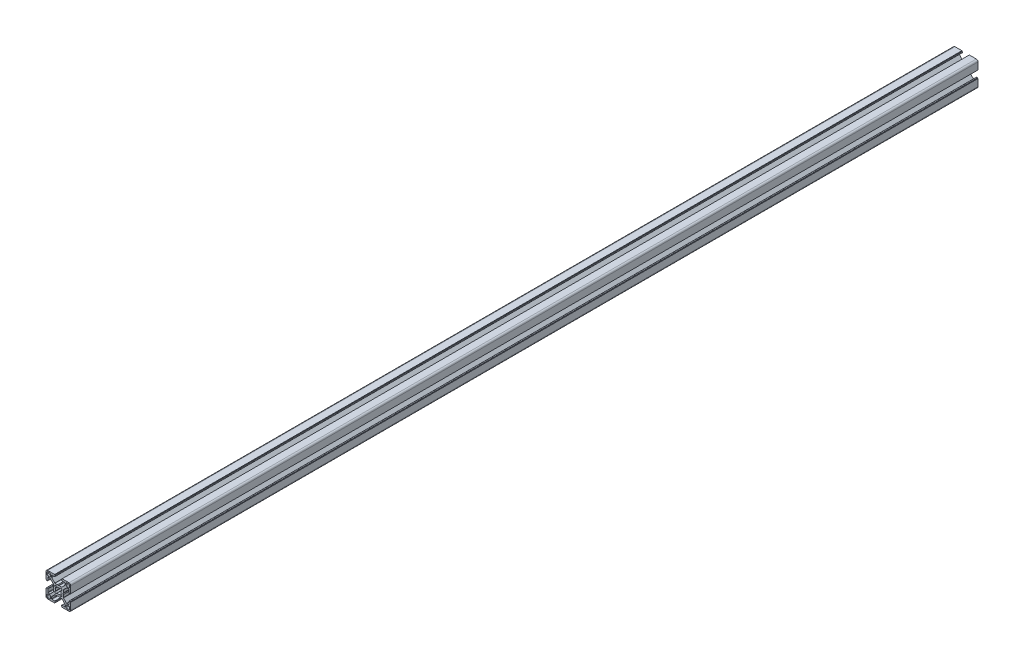
SolidWorks part; units mm, degrees
ref_plane "Front Plane" through (0, 0, 0) normal (0, 0, 1) x (1, 0, 0)
ref_plane "Top Plane" through (0, 0, 0) normal (0, 1, 0) x (1, 0, 0)
ref_plane "Right Plane" through (0, 0, 0) normal (1, 0, 0) x (0, 0, -1)
sketch "Sketch1" plane through (0, 0, 0) normal (0, 0, 1) x (1, 0, 0)
  line L0 (-15, 0) -> (15, 0) construction
  line L1 (0, -15) -> (0, 15) construction
  line L2 (-4.5, 15) -> (4.5, 15) construction
  line L3 (-4, -15) -> (4, -15) construction
  line L4 (-4.5, 15) -> (-4.5, 14.5)
  line L5 (-4.5, 14.5) -> (-4, 14.5)
  line L6 (-4, 14.5) -> (-4, 13.29)
  line L7 (-4.5, 12.79) -> (-7.7675, 12.79)
  line L8 (-8.2675, 12.29) -> (-8.2675, 10.2707)
  line L9 (-8.1211, 9.9171) -> (-4.3504, 6.1464)
  line L10 (-3.9968, 6) -> (0, 6)
  line L11 (0, 0) -> (-15, 15) construction
  line L12 (-4.5, 15) -> (-12.968, 15)
  line L14 (-12.705, 9.5135) -> (-10.5135, 9.5135)
  line L15 (-13.705, 10.5135) -> (-13.705, 12.705)
  line L16 (-12.705, 13.705) -> (-10.5135, 13.705)
  line L17 (-9.5135, 10.5135) -> (-9.5135, 12.705)
  line L18 (-13.705, 9.5135) -> (-9.5135, 13.705) construction
  line L19 (-13.705, 13.705) -> (-9.5135, 9.5135) construction
  line L20 (-3.1568, 4.5038) -> (-1.5303, 3.1477) construction
  line L21 (-4.5038, 3.1568) -> (-3.1477, 1.5303) construction
  line L22 (-6, 3.9968) -> (-6, 0)
  line L23 (-9.9171, 8.1211) -> (-6.1464, 4.3504)
  line L24 (-15, 4.5) -> (-15, 12.968)
  line L25 (-12.29, 8.2675) -> (-10.2707, 8.2675)
  line L26 (-12.79, 4.5) -> (-12.79, 7.7675)
  line L27 (-14.5, 4) -> (-13.29, 4)
  line L28 (-14.5, 4.5) -> (-14.5, 4)
  line L29 (-15, 4.5) -> (-14.5, 4.5)
  circle A0 centre (0, 0) radius 3.5
  arc A1 (-12.968, 15) -> (-15, 12.968) centre (-12.968, 12.968) ccw
  circle A2 centre (0, 0) radius 5.5 construction
  arc A3 (-10.5135, 9.5135) -> (-9.5135, 10.5135) centre (-10.5135, 10.5135) ccw
  arc A4 (-13.705, 12.705) -> (-12.705, 13.705) centre (-12.705, 12.705) cw
  arc A5 (-10.5135, 13.705) -> (-9.5135, 12.705) centre (-10.5135, 12.705) cw
  arc A6 (-12.705, 9.5135) -> (-13.705, 10.5135) centre (-12.705, 10.5135) cw
  arc A7 (-12.79, 4.5) -> (-13.29, 4) centre (-13.29, 4.5) cw
  arc A8 (-12.29, 8.2675) -> (-12.79, 7.7675) centre (-12.29, 7.7675) ccw
  arc A9 (-9.9171, 8.1211) -> (-10.2707, 8.2675) centre (-10.2707, 7.7675) ccw
  arc A10 (-6, 3.9968) -> (-6.1464, 4.3504) centre (-6.5, 3.9968) ccw
  arc A11 (-4.3504, 6.1464) -> (-3.9968, 6) centre (-3.9968, 6.5) ccw
  arc A12 (-4, 13.29) -> (-4.5, 12.79) centre (-4.5, 13.29) cw
  arc A13 (-7.7675, 12.79) -> (-8.2675, 12.29) centre (-7.7675, 12.29) ccw
  arc A14 (-8.2675, 10.2707) -> (-8.1211, 9.9171) centre (-7.7675, 10.2707) ccw
  point P4 (0, 0)
  point P8 (0, 0)
  point P13 (0, 15)
  point P15 (0, -15)
  point P16 (0, 6)
  point P23 (-11.6092, 11.6093)
  point P26 (0, 6)
  point P62 (-12.79, 4)
  point P65 (-12.79, 8.2675)
  point P68 (-10.0636, 8.2675)
  point P71 (-6, 4.2039)
  point P74 (-4.2039, 6)
  point P77 (-4, 12.79)
  point P80 (-8.2675, 12.79)
  point P83 (-8.2675, 10.0636)
  dimension "Center Hole Diameter" = 7
  dimension "D11" = 2.032
  dimension "D9" = 11
  dimension "D13" = 1
  dimension "D14" = 0.5
  dimension "Rail Height" = 30
  dimension "Rail Width" = 30
  dimension "T-Slot Width" = 8
  dimension "T-Slot Depth" = 9
  dimension "D1" = 9
  dimension "D2" = 45
  dimension "D3" = 8
  dimension "D4" = 2.21
  dimension "D5" = 16.535
  dimension "D7" = 2.54
  dimension "D6" = 1.295
  dimension "D8" = 1.246
  dimension "D10" = 10.36
  dimension "D12" = 1.905
sketch "Sketch2" plane through (0, 0, 0) normal (1, 0, 0) x (0, 0, -1)
  line L0 (-76.2, 0) -> (76.2, 0) construction
  line L2 (0, -15) -> (0, 15) construction
  line L3 (0, -15) -> (0, 15) construction
  line L4 (-76.2, -15) -> (-76.2, 15) construction
  line L5 (76.2, -15) -> (76.2, 15) construction
  point P0 (-38.7, 0)
  point P3 (0, 0)
  point P4 (38.7, 0)
  point P12 (-76.2, 0)
  point P14 (76.2, 0)
  dimension "Length" = 152.4
  dimension "D1" = 37.5
sketch "Sketch3" plane through (0, 0, 0) normal (0, 0, 1) x (1, 0, 0)
  line L0 (-4.5038, 3.1568) -> (-3.1477, 1.5303)
  line L1 (0, 3.5) -> (0, 5.5)
  line L2 (-5.5, 0) -> (-3.5, 0)
  line L7 (-6, 3.9968) -> (-6, 0) construction
  line L31 (-9.9171, 8.1211) -> (-6.1464, 4.3504) construction
  line L117 (-12.29, 8.2675) -> (-10.2707, 8.2675) construction
  line L118 (-12.79, 4.5) -> (-12.79, 7.7675) construction
  line L157 (-12.705, 9.5135) -> (-10.5135, 9.5135)
  line L158 (-9.5135, 10.5135) -> (-9.5135, 12.705)
  line L163 (-10.5135, 13.705) -> (-12.705, 13.705)
  line L164 (-13.705, 12.705) -> (-13.705, 10.5135)
  line L165 (-12.705, 9.5135) -> (-10.5135, 9.5135)
  line L166 (-9.5135, 10.5135) -> (-9.5135, 12.705)
  line L167 (-10.5135, 13.705) -> (-12.705, 13.705)
  line L168 (-13.705, 12.705) -> (-13.705, 10.5135)
  line L169 (-14.5, 4) -> (-13.29, 4) construction
  line L170 (-14.5, 4.5) -> (-14.5, 4) construction
  line L171 (-15, 4.5) -> (-14.5, 4.5) construction
  line L172 (-15, 4.5) -> (-15, 12.968) construction
  line L173 (-4.5, 15) -> (-12.968, 15) construction
  line L174 (-4.5, 15) -> (-4.5, 14.5) construction
  line L175 (-4.5, 14.5) -> (-4, 14.5) construction
  line L176 (-4, 14.5) -> (-4, 13.29) construction
  line L177 (-4.5, 12.79) -> (-7.7675, 12.79) construction
  line L178 (-8.2675, 12.29) -> (-8.2675, 10.2707) construction
  line L179 (-8.1211, 9.9171) -> (-4.3504, 6.1464) construction
  line L180 (-3.9968, 6) -> (0, 6) construction
  line L181 (-6, 3.9968) -> (-6, 0.866)
  line L182 (-9.9171, 8.1211) -> (-6.1464, 4.3504)
  line L183 (-12.29, 8.2675) -> (-10.2707, 8.2675)
  line L184 (-12.79, 4.5) -> (-12.79, 7.7675)
  line L185 (-14.5, 4) -> (-13.29, 4)
  line L186 (-14.5, 4.5) -> (-14.5, 4)
  line L187 (-15, 4.5) -> (-14.5, 4.5)
  line L188 (-15, 4.5) -> (-15, 12.968)
  line L189 (-4.5, 15) -> (-12.968, 15)
  line L190 (-4.5, 15) -> (-4.5, 14.5)
  line L191 (-4.5, 14.5) -> (-4, 14.5)
  line L192 (-4, 14.5) -> (-4, 13.29)
  line L193 (-4.5, 12.79) -> (-7.7675, 12.79)
  line L194 (-8.2675, 12.29) -> (-8.2675, 10.2707)
  line L195 (-8.1211, 9.9171) -> (-4.3504, 6.1464)
  line L196 (-3.9968, 6) -> (-0.866, 6)
  line L197 (-0.866, 6) -> (0, 5.5)
  line L198 (0, -15) -> (0, 15) construction
  line L199 (0, 0) -> (-15, 15) construction
  line L200 (0, 0) -> (-15, 15) construction
  line L201 (-3.1568, 4.5038) -> (-1.5303, 3.1477) construction
  line L202 (-3.1568, 4.5038) -> (-1.5303, 3.1477)
  line L203 (-6, 0.866) -> (-5.5, 0)
  line L204 (-15, 0) -> (15, 0) construction
  line L205 (-15, 0) -> (15, 0) construction
  line L206 (0, -15) -> (0, 15) construction
  arc A0 (-3.5, 0) -> (-3.1477, 1.5303) centre (0, 0) cw
  arc A10 (-6, 3.9968) -> (-6.1464, 4.3504) centre (-6.5, 3.9968) ccw construction
  circle A16 centre (0, 0) radius 3.5
  arc A18 (0, 3.5) -> (-1.5303, 3.1477) centre (0, 0) ccw
  arc A20 (-9.9171, 8.1211) -> (-10.2707, 8.2675) centre (-10.2707, 7.7675) ccw construction
  arc A22 (-12.29, 8.2675) -> (-12.79, 7.7675) centre (-12.29, 7.7675) ccw construction
  arc A28 (-13.29, 4) -> (-12.79, 4.5) centre (-13.29, 4.5) ccw construction
  arc A29 (-10.5135, 9.5135) -> (-9.5135, 10.5135) centre (-10.5135, 10.5135) ccw
  arc A30 (-9.5135, 12.705) -> (-10.5135, 13.705) centre (-10.5135, 12.705) ccw
  arc A31 (-12.705, 13.705) -> (-13.705, 12.705) centre (-12.705, 12.705) ccw
  arc A32 (-13.705, 10.5135) -> (-12.705, 9.5135) centre (-12.705, 10.5135) ccw
  arc A33 (-10.5135, 9.5135) -> (-9.5135, 10.5135) centre (-10.5135, 10.5135) ccw
  arc A34 (-9.5135, 12.705) -> (-10.5135, 13.705) centre (-10.5135, 12.705) ccw
  arc A35 (-12.705, 13.705) -> (-13.705, 12.705) centre (-12.705, 12.705) ccw
  arc A36 (-13.705, 10.5135) -> (-12.705, 9.5135) centre (-12.705, 10.5135) ccw
  arc A37 (-12.968, 15) -> (-15, 12.968) centre (-12.968, 12.968) ccw construction
  arc A38 (-4.5, 12.79) -> (-4, 13.29) centre (-4.5, 13.29) ccw construction
  arc A39 (-7.7675, 12.79) -> (-8.2675, 12.29) centre (-7.7675, 12.29) ccw construction
  arc A40 (-8.2675, 10.2707) -> (-8.1211, 9.9171) centre (-7.7675, 10.2707) ccw construction
  arc A41 (-4.3504, 6.1464) -> (-3.9968, 6) centre (-3.9968, 6.5) ccw construction
  arc A42 (-6, 3.9968) -> (-6.1464, 4.3504) centre (-6.5, 3.9968) ccw
  arc A43 (-9.9171, 8.1211) -> (-10.2707, 8.2675) centre (-10.2707, 7.7675) ccw
  arc A44 (-12.29, 8.2675) -> (-12.79, 7.7675) centre (-12.29, 7.7675) ccw
  arc A45 (-13.29, 4) -> (-12.79, 4.5) centre (-13.29, 4.5) ccw
  arc A46 (-12.968, 15) -> (-15, 12.968) centre (-12.968, 12.968) ccw
  arc A47 (-4.5, 12.79) -> (-4, 13.29) centre (-4.5, 13.29) ccw
  arc A48 (-7.7675, 12.79) -> (-8.2675, 12.29) centre (-7.7675, 12.29) ccw
  arc A49 (-8.2675, 10.2707) -> (-8.1211, 9.9171) centre (-7.7675, 10.2707) ccw
  arc A50 (-4.3504, 6.1464) -> (-3.9968, 6) centre (-3.9968, 6.5) ccw
  circle A51 centre (0, 0) radius 5.5 construction
  arc A52 (-3.1568, 4.5038) -> (-4.5038, 3.1568) centre (0, 0) ccw
  dimension "D3" = 60
  dimension "D4" = 60
  dimension "D1" = 0
  dimension "D2" = 0
extrude "Boss-Extrude1" add sketch "Sketch3" along normal mid plane 1100
pattern_circular "CirPattern1" count 4 over 360 about axis through (0, 0, 0) along (0, 0, 1) of "Boss-Extrude1"
ref_plane "Contact Plane1" through (15, 0, 0) normal (1, 0, 0) x (0, 0, -1)
ref_plane "Contact Plane2" through (0, -15, 0) normal (0, 1, 0) x (1, 0, 0)
ref_plane "Contact Plane3" through (-15, 0, 0) normal (1, 0, 0) x (0, 0, -1)
ref_plane "Contact Plane4" through (0, 15, 0) normal (0, 1, 0) x (1, 0, 0)
equation "\"D1@Sketch2\" = \"Rail Height@Sketch1\" * 1.25"
equation "\"D1@Sketch1\"=\"T-Slot Width@Sketch1\"+1mm"
equation "\"D3@Sketch1\"=\"T-Slot Width@Sketch1\""
equation "\"D1@Boss-Extrude1\"=\"length\""
equation "\"length\"= 1100"
